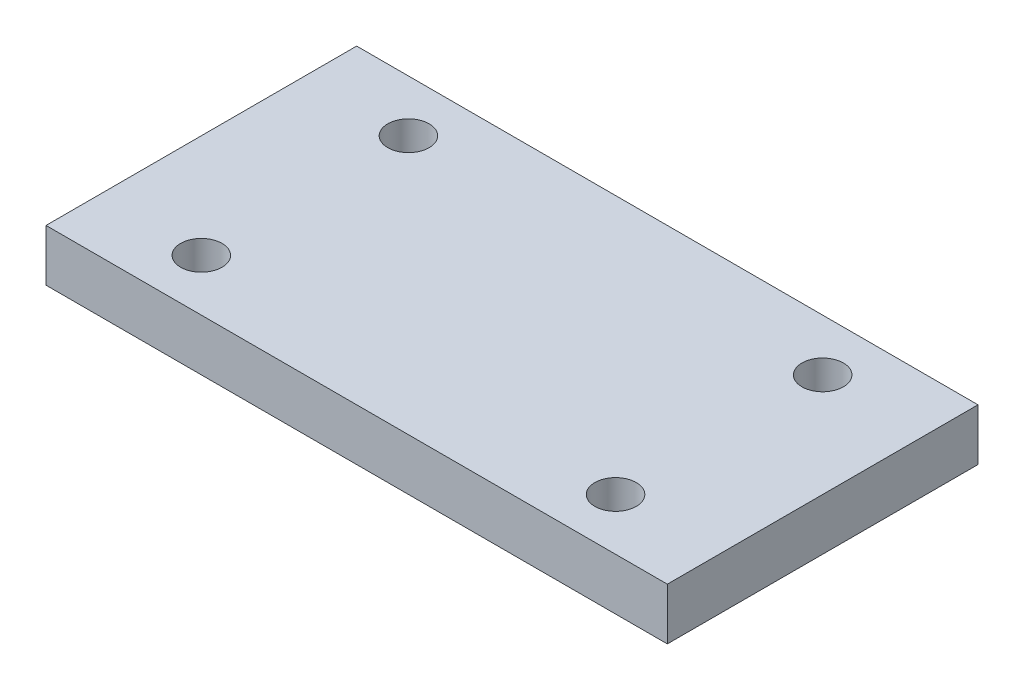
SolidWorks part; units mm, degrees
ref_plane "前视基准面" through (0, 0, 0) normal (0, 0, 1) x (1, 0, 0)
ref_plane "上视基准面" through (0, 0, 0) normal (0, 1, 0) x (1, 0, 0)
ref_plane "右视基准面" through (0, 0, 0) normal (1, 0, 0) x (0, 0, -1)
sketch "草图1" plane through (0, 0, 0) normal (0, 1, 0) x (1, 0, 0)
  line L1 (-30, 15) -> (30, 15)
  line L2 (-30, 15) -> (-30, -15)
  line L3 (-30, -15) -> (30, -15)
  line L4 (30, 15) -> (30, -15)
  line L5 (-30, 15) -> (30, -15) construction
  line L6 (-30, -15) -> (30, 15) construction
  line L7 (-20, 10) -> (20, 10)
  line L8 (-20, 10) -> (-20, -10)
  line L9 (-20, -10) -> (20, -10)
  line L10 (20, 10) -> (20, -10)
  line L11 (-20, 10) -> (20, -10) construction
  line L12 (-20, -10) -> (20, 10) construction
  circle A0 centre (-20, 10) radius 2
  circle A1 centre (20, 10) radius 2
  circle A2 centre (-20, -10) radius 2
  circle A3 centre (20, -10) radius 2
  point P0 (0, 0)
  point P5 (0, 0)
  dimension "D1" = 60
  dimension "D2" = 30
  dimension "D3" = 40
  dimension "D4" = 20
extrude "凸台-拉伸1" add sketch "草图1" along normal blind 5 contours L4 L1 L2 L3 A3 L9 A2 L8 A0 L7 A1 L10 | A3 L10 A1 L7 A0 L8 A2 L9
